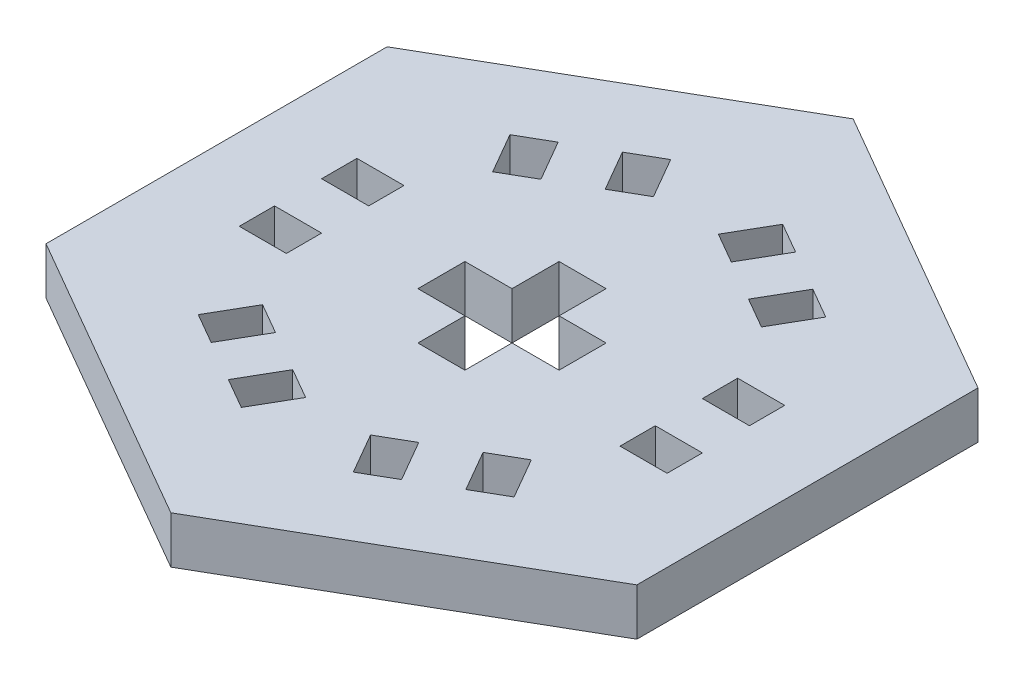
SolidWorks part; units mm, degrees
ref_plane "Front Plane" through (0, 0, 0) normal (0, 0, 1) x (1, 0, 0)
ref_plane "Top Plane" through (0, 0, 0) normal (0, 1, 0) x (1, 0, 0)
ref_plane "Right Plane" through (0, 0, 0) normal (1, 0, 0) x (0, 0, -1)
sketch "Sketch1" plane through (0, 0, 0) normal (0, 1, 0) x (1, 0, 0)
  line L0 (-41.6269, -5.1368) -> (-9.74, -23.5467)
  line L1 (-9.74, -23.5467) -> (22.1469, -5.1368)
  line L2 (22.1469, -5.1368) -> (22.1469, 31.6831)
  line L3 (22.1469, 31.6831) -> (-9.74, 50.093)
  line L4 (-9.74, 50.093) -> (-41.6269, 31.6831)
  line L5 (-41.6269, 31.6831) -> (-41.6269, -5.1368)
  line L6 (-41.6269, 13.2732) -> (22.1469, 13.2732) construction
  line L7 (-9.74, -13.3867) -> (13.3481, -0.0568) construction
  line L8 (13.3481, -0.0568) -> (13.3481, 26.6031) construction
  line L9 (13.3481, 26.6031) -> (-9.74, 39.933) construction
  line L10 (-9.74, 39.933) -> (-32.8281, 26.6031) construction
  line L11 (-32.8281, 26.6031) -> (-32.8281, -0.0568) construction
  line L12 (-32.8281, -0.0568) -> (-9.74, -13.3867) construction
  line L13 (-9.74, 50.093) -> (-9.74, -23.5467) construction
  line L14 (-15.7848, 36.443) -> (-13.2448, 32.0436)
  line L15 (-32.8281, 19.6232) -> (-27.7481, 19.6232)
  line L16 (-32.8281, 19.6232) -> (-32.8281, 15.8132)
  line L17 (-32.8281, 15.8132) -> (-27.7481, 15.8132)
  line L18 (-27.7481, 19.6232) -> (-27.7481, 15.8132)
  line L19 (-32.8281, 6.9232) -> (-27.7481, 6.9232)
  line L20 (-32.8281, 6.9232) -> (-32.8281, 10.7332)
  line L21 (-32.8281, 10.7332) -> (-27.7481, 10.7332)
  line L22 (-27.7481, 6.9232) -> (-27.7481, 10.7332)
  line L23 (-15.7848, 36.443) -> (-19.0844, 34.538)
  line L24 (-19.0844, 34.538) -> (-16.5444, 30.1386)
  line L25 (-13.2448, 32.0436) -> (-16.5444, 30.1386)
  line L26 (-26.7833, 30.093) -> (-24.2433, 25.6936)
  line L27 (-26.7833, 30.093) -> (-23.4838, 31.998)
  line L28 (-23.4838, 31.998) -> (-20.9438, 27.5986)
  line L29 (-24.2433, 25.6936) -> (-20.9438, 27.5986)
  line L30 (7.3033, 30.093) -> (4.7633, 25.6936)
  line L31 (7.3033, 30.093) -> (4.0037, 31.998)
  line L32 (4.0037, 31.998) -> (1.4637, 27.5986)
  line L33 (4.7633, 25.6936) -> (1.4637, 27.5986)
  line L34 (-3.6952, 36.443) -> (-6.2352, 32.0436)
  line L35 (-3.6952, 36.443) -> (-0.3957, 34.538)
  line L36 (-0.3957, 34.538) -> (-2.9357, 30.1386)
  line L37 (-6.2352, 32.0436) -> (-2.9357, 30.1386)
  line L38 (13.3481, 6.9232) -> (8.2681, 6.9232)
  line L39 (13.3481, 6.9232) -> (13.3481, 10.7332)
  line L40 (13.3481, 10.7332) -> (8.2681, 10.7332)
  line L41 (8.2681, 6.9232) -> (8.2681, 10.7332)
  line L42 (13.3481, 19.6232) -> (8.2681, 19.6232)
  line L43 (13.3481, 19.6232) -> (13.3481, 15.8132)
  line L44 (13.3481, 15.8132) -> (8.2681, 15.8132)
  line L45 (8.2681, 19.6232) -> (8.2681, 15.8132)
  line L46 (-3.6952, -9.8967) -> (-6.2352, -5.4973)
  line L47 (-3.6952, -9.8967) -> (-0.3957, -7.9917)
  line L48 (-0.3957, -7.9917) -> (-2.9357, -3.5923)
  line L49 (-6.2352, -5.4973) -> (-2.9357, -3.5923)
  line L50 (7.3033, -3.5467) -> (4.7633, 0.8527)
  line L51 (7.3033, -3.5467) -> (4.0037, -5.4517)
  line L52 (4.0037, -5.4517) -> (1.4637, -1.0523)
  line L53 (4.7633, 0.8527) -> (1.4637, -1.0523)
  line L54 (-26.7833, -3.5467) -> (-24.2433, 0.8527)
  line L55 (-26.7833, -3.5467) -> (-23.4838, -5.4517)
  line L56 (-23.4838, -5.4517) -> (-20.9438, -1.0523)
  line L57 (-24.2433, 0.8527) -> (-20.9438, -1.0523)
  line L58 (-15.7848, -9.8967) -> (-13.2448, -5.4973)
  line L59 (-15.7848, -9.8967) -> (-19.0844, -7.9917)
  line L60 (-19.0844, -7.9917) -> (-16.5444, -3.5923)
  line L61 (-13.2448, -5.4973) -> (-16.5444, -3.5923)
  circle A0 centre (-9.74, 13.2732) radius 31.8869 construction
  circle A1 centre (-9.74, 13.2732) radius 23.0881 construction
  point P8 (-9.74, 13.2732)
  point P69 (-9.74, 13.2732)
  dimension "D1" = 36.8198
  dimension "D2" = 26.6598
  dimension "D3" = 5.08
  dimension "D4" = 5.08
  dimension "D5" = 3.81
  dimension "D6" = 3.81
  dimension "D7" = 2.54
  dimension "D8" = 2.54
  dimension "D9" = 6
extrude "Boss-Extrude1" add sketch "Sketch1" along normal blind 5.08
sketch "Sketch2" plane through (0, 5.08, 0) normal (0, 1, 0) x (1, 0, 0)
  line L0 (-9.74, 50.093) -> (-9.74, -23.5467) construction
  line L1 (-41.6269, 13.2732) -> (22.1469, 13.2732) construction
  line L2 (-41.6269, 31.6831) -> (-41.6269, -5.1368) construction
  line L3 (22.1469, -5.1368) -> (22.1469, 31.6831) construction
  line L4 (-9.74, 20.8932) -> (-7.2, 20.8932)
  line L5 (-7.2, 20.8932) -> (-7.2, 15.8132)
  line L6 (-7.2, 15.8132) -> (-2.12, 15.8132)
  line L7 (-2.12, 15.8132) -> (-2.12, 13.2732)
  line L8 (-2.12, 13.2732) -> (-2.12, 10.7332)
  line L9 (33.4715, 27.6939) -> (33.6739, 27.6939)
  line L10 (-2.12, 10.7332) -> (-7.2, 10.7332)
  line L11 (-7.2, 10.7332) -> (-7.2, 5.6532)
  line L12 (-7.2, 5.6532) -> (-9.74, 5.6532)
  line L13 (-9.74, 5.6532) -> (-12.28, 5.6532)
  line L14 (-12.28, 5.6532) -> (-12.28, 10.7332)
  line L15 (-12.28, 10.7332) -> (-17.36, 10.7332)
  line L16 (-17.36, 10.7332) -> (-17.36, 13.2732)
  line L17 (-17.36, 13.2732) -> (-17.36, 15.8132)
  line L18 (-17.36, 15.8132) -> (-12.28, 15.8132)
  line L19 (-12.28, 15.8132) -> (-12.28, 20.8932)
  line L20 (-12.28, 20.8932) -> (-9.74, 20.8932)
  point P10 (-9.74, 13.2732)
  point P36 (-9.74, 13.2732)
  dimension "D1" = 2.54
  dimension "D2" = 2.54
  dimension "D3" = 5.08
  dimension "D4" = 5.08
  dimension "D5" = 4
extrude "Cut-Extrude1" cut sketch "Sketch2" against normal blind 5.08 contours L20 L19 L18 L17 L16 L15 L14 L13 L12 L11 L10 L8 L7 L6 L5 L4
